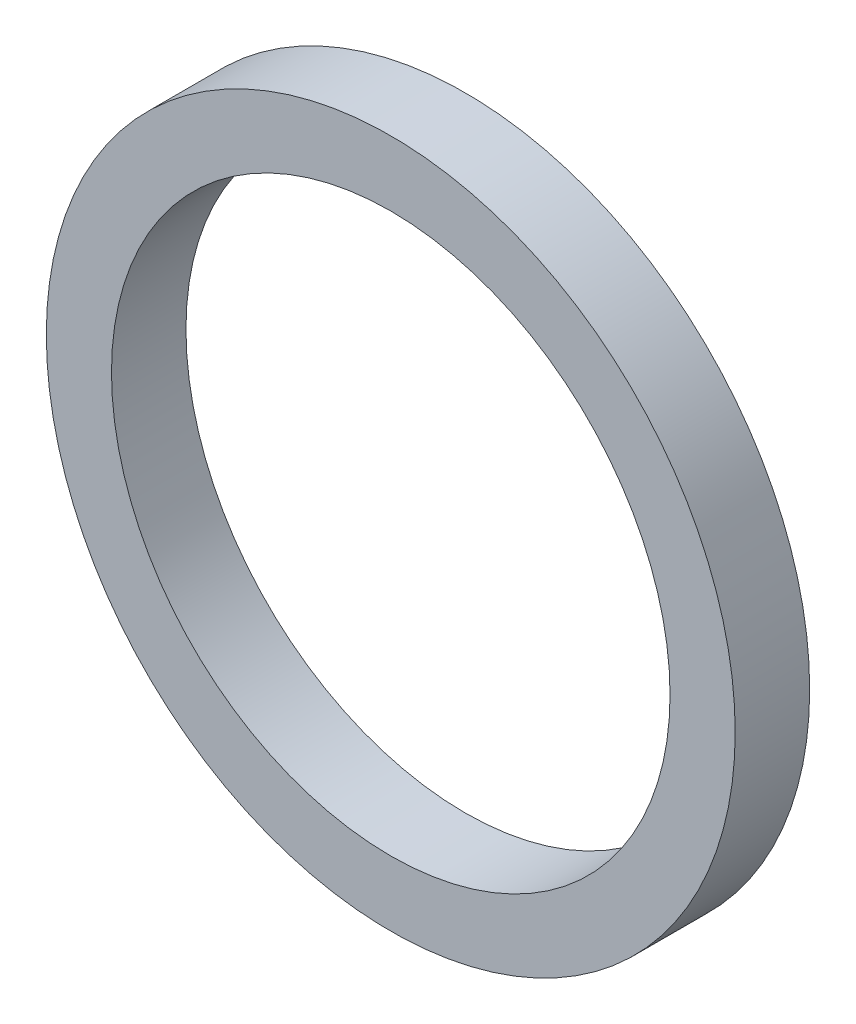
SolidWorks part; units mm, degrees
material "6061 合金"
ref_plane "前视基准面" through (0, 0, 0) normal (0, 0, 1) x (1, 0, 0)
ref_plane "上视基准面" through (0, 0, 0) normal (0, 1, 0) x (1, 0, 0)
ref_plane "右视基准面" through (0, 0, 0) normal (1, 0, 0) x (0, 0, -1)
other "Configuration Table"
sketch "草图1" plane through (0, 0, 0) normal (0, 0, 1) x (1, 0, 0)
  circle A0 centre (0, 0) radius 15
  circle A1 centre (0, 0) radius 18.5
  dimension "D1" = 30
  dimension "D2" = 37
extrude "凸台-拉伸1" add sketch "草图1" along normal blind 4
